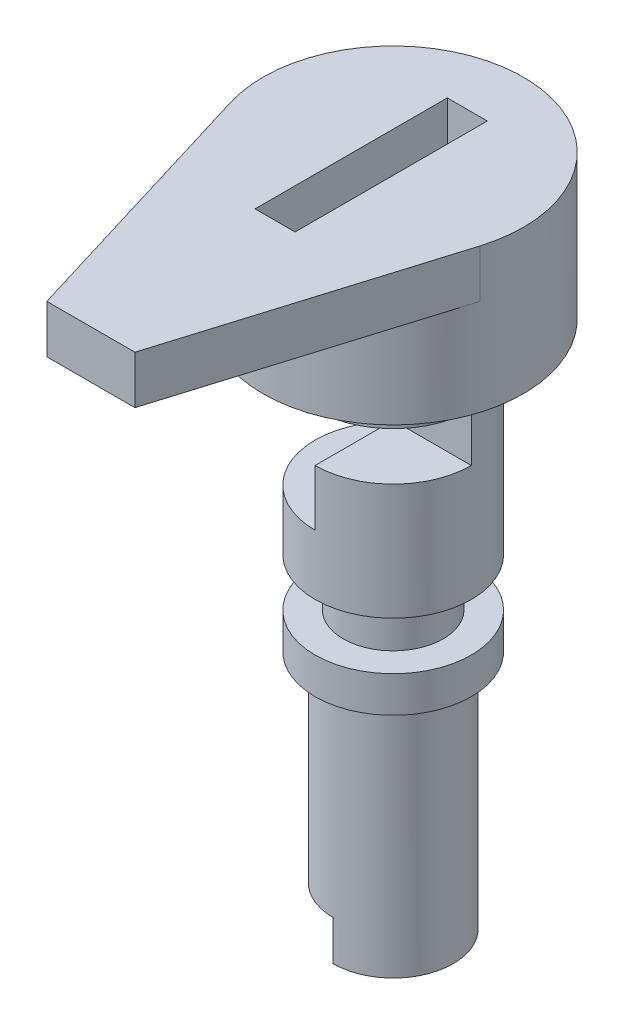
SolidWorks part; units mm, degrees
material "ABS"
ref_plane "Front Plane" through (0, 0, 0) normal (0, 0, 1) x (1, 0, 0)
ref_plane "Top Plane" through (0, 0, 0) normal (0, 1, 0) x (1, 0, 0)
ref_plane "Right Plane" through (0, 0, 0) normal (1, 0, 0) x (0, 0, -1)
ref_axis "CentralAxis" through (0, 4.44, 0) along (0, -1, 0)
sketch "BaseS" plane through (0, 0, 0) normal (0, 1, 0) x (1, 0, 0)
  circle A0 centre (0, 0) radius 3.25
  dimension "Dia" = 6.5
extrude "Base" add sketch "BaseS" along normal blind 2.4
sketch "TopShaftS" plane through (0, 0, 0) normal (0, -1, 0) x (-1, 0, 0)
  circle A0 centre (0, 0) radius 1.95
  dimension "Dia" = 3.9
extrude "TopShaft" add sketch "TopShaftS" along normal blind 7.2
sketch "MainSlotS" plane through (0, 0, 0) normal (0, 0, 1) x (1, 0, 0)
  line L0 (-1.95, 0) -> (-1.95, -7.2) construction
  line L1 (0, -3.6) -> (-1.95, -3.6)
  line L2 (0, -3.6) -> (0, -1)
  line L3 (0, -1) -> (-1.95, -1)
  line L4 (-1.95, -3.6) -> (-1.95, -1)
  line L5 (0, -3.6) -> (-1.95, -1) construction
  line L6 (0, -1) -> (-1.95, -3.6) construction
  line L7 (-3.25, 0) -> (3.25, 0) construction
  point P0 (-0.975, -2.3)
  dimension "YLoc" = 1
  dimension "Height" = 2.6
extrude "MainSlot" cut sketch "MainSlotS" against normal through all both and the other way through all
sketch "SmallSlotS" plane through (0, 0, 0) normal (1, 0, 0) x (0, 0, -1)
  line L0 (-1.95, 0) -> (-1.95, -1) construction
  line L1 (0, -2.2) -> (-1.95, -2.2)
  line L2 (0, -2.2) -> (0, -1)
  line L3 (0, -1) -> (-1.95, -1)
  line L4 (-1.95, -2.2) -> (-1.95, -1)
  line L5 (0, -2.2) -> (-1.95, -1) construction
  line L6 (0, -1) -> (-1.95, -2.2) construction
  line L7 (-1.95, -1) -> (-1.95, -3.6) construction
  line L8 (1.95, -1) -> (-1.95, -1) construction
  point P0 (-0.975, -1.6)
  point P7 (-1.95, -1)
  point P10 (-1.95, -1.3749)
  dimension "Height" = 1.2
extrude "SmallSlot" cut sketch "SmallSlotS" against normal through all both and the other way through all
sketch "O-RingGrooveS" plane through (0, 0, 0) normal (0, 0, 1) x (1, 0, 0)
  line L0 (-1.95, -3.6) -> (-1.95, -7.2) construction
  line L1 (-1.95, -5.1) -> (-1.25, -5.1)
  line L2 (-1.95, -5.1) -> (-1.95, -6.3)
  line L3 (-1.95, -6.3) -> (-1.25, -6.3)
  line L4 (-1.25, -5.1) -> (-1.25, -6.3)
  line L5 (0, -3.6) -> (-1.95, -3.6) construction
  line L6 (0, 0) -> (0, -7.2) construction
  line L7 (-1.95, -7.2) -> (1.95, -7.2) construction
  dimension "Width" = 1.2
  dimension "YLoc" = 1.5
  dimension "ID" = 2.5
revolve "O-RingGroove" cut sketch "O-RingGrooveS" angle 360 about L6
sketch "BottomShaftS" plane through (0, -7.2, 0) normal (0, -1, 0) x (1, 0, 0)
  circle A0 centre (0, 0) radius 1.5
  dimension "Dia" = 3
extrude "BottomShaft" add sketch "BottomShaftS" along normal blind 6
sketch "TabS" plane through (0, 2.4, 0) normal (0, 1, 0) x (1, 0, 0)
  line L0 (-3.1093, -0.946) -> (-1.1, -7.55)
  line L1 (-1.1, -7.55) -> (1.1, -7.55)
  line L2 (1.1, -7.55) -> (3.1093, -0.946)
  line L3 (0, -7.55) -> (0, 0) construction
  circle A1 centre (0, 0) radius 3.25
  arc A2 (3.1093, -0.946) -> (-3.1093, -0.946) centre (0, 0) ccw
  point P8 (0, 3.25)
  dimension "Length" = 10.8
  dimension "EndWidth" = 2.2
  dimension "D1" = 0
extrude "Tab" add sketch "TabS" along normal blind 1.2
sketch "ScrewCutS" plane through (0, 0, 0) normal (0, 0, 1) x (1, 0, 0)
  line L0 (-0.01, -13.2) -> (-1.5, -12.2)
  line L2 (-1.5, -7.2) -> (-1.5, -13.2) construction
  line L3 (-1.5, -12.2) -> (-1.5, -13.2)
  line L4 (-1.5, -13.2) -> (-0.01, -13.2)
  line L5 (0, 4.44) -> (0, -14.04) construction
  point P0 (-0.0245, -13.2)
  dimension "Height" = 1
  dimension "Spacing" = 0.01
revolve "ScrewCut" cut sketch "ScrewCutS" angle 180 mid plane about axis through (0, 4.44, 0) along (0, -1, 0)
sketch "KeyWayS" plane through (0, 3.6, 0) normal (0, 1, 0) x (1, 0, 0)
  line L0 (-1.1, -7.55) -> (1.1, -7.55) construction
  line L1 (-0.5, 1.85) -> (0.5, 1.85)
  line L2 (-0.5, 1.85) -> (-0.5, -2.95)
  line L3 (-0.5, -2.95) -> (0.5, -2.95)
  line L4 (0.5, 1.85) -> (0.5, -2.95)
  line L5 (-0.5, 1.85) -> (0.5, -2.95) construction
  line L6 (-0.5, -2.95) -> (0.5, 1.85) construction
  line L7 (0, -7.55) -> (0, -2.95) construction
  point P0 (0, -0.55)
  dimension "Width" = 1
  dimension "Length" = 4.8
  dimension "YLoc" = 4.6
extrude "KeyWay" cut sketch "KeyWayS" against normal blind 1
